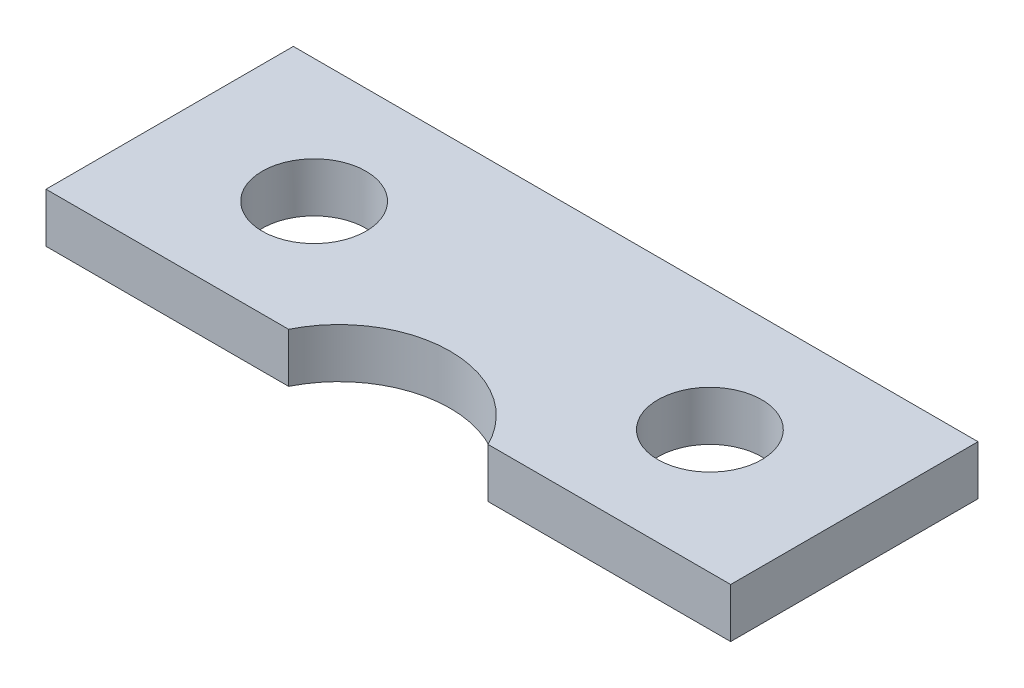
SolidWorks part; units mm, degrees
material "ABS"
ref_plane "前视基准面" through (0, 0, 0) normal (0, 0, 1) x (1, 0, 0)
ref_plane "上视基准面" through (0, 0, 0) normal (0, 1, 0) x (1, 0, 0)
ref_plane "右视基准面" through (0, 0, 0) normal (1, 0, 0) x (0, 0, -1)
sketch "Sketch1" plane through (0, 0, 0) normal (0, 1, 0) x (1, 0, 0)
  line L1 (-13.84, 5) -> (13.84, 5)
  line L2 (-13.84, 5) -> (-13.84, -5)
  line L3 (-13.84, -5) -> (13.84, -5)
  line L4 (13.84, 5) -> (13.84, -5)
  line L5 (0, -5) -> (0, 5) construction
  line L6 (-13.84, 0) -> (13.84, 0) construction
  point P0 (0, 0)
  dimension "D1" = 27.68
  dimension "D2" = 10
extrude "Boss-Extrude1" add sketch "Sketch1" along normal blind 2
sketch "Sketch2" plane through (0, 2, 0) normal (0, 1, 0) x (1, 0, 0)
  line L0 (0, 0) -> (0, 2.8927) construction
  circle A0 centre (8, 0) radius 2.1
  circle A1 centre (-8, 0) radius 2.1
  dimension "D1" = 4.2
  dimension "D2" = 8
extrude "Cut-Extrude1" cut sketch "Sketch2" against normal up to next
sketch "Sketch3" plane through (0, 0, 0) normal (0, -1, 0) x (1, 0, 0)
  circle A0 centre (0, 7) radius 4.5
  dimension "D1" = 9
  dimension "D2" = 7
extrude "Cut-Extrude2" cut sketch "Sketch3" against normal up to next
